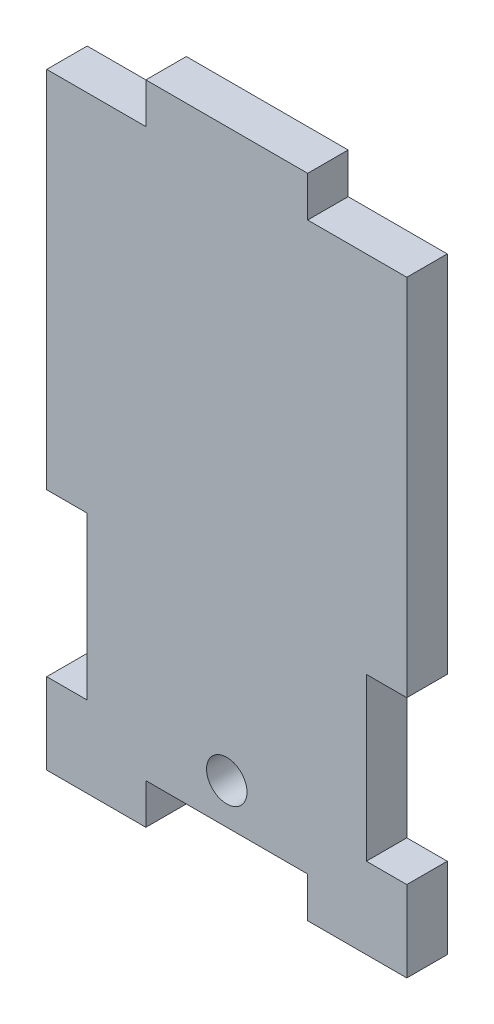
SolidWorks part; units mm, degrees
ref_plane "Front Plane" through (0, 0, 0) normal (0, 0, 1) x (1, 0, 0)
ref_plane "Top Plane" through (0, 0, 0) normal (0, 1, 0) x (1, 0, 0)
ref_plane "Right Plane" through (0, 0, 0) normal (1, 0, 0) x (0, 0, -1)
sketch "Sketch1" plane through (0, 0, 0) normal (0, 0, 1) x (1, 0, 0)
  line L1 (0, 0) -> (44.5, 0)
  line L2 (0, 0) -> (0, 80)
  line L3 (0, 80) -> (44.5, 80)
  line L4 (44.5, 0) -> (44.5, 80)
  line L5 (12.25, 0) -> (32.25, 0)
  line L6 (12.25, 0) -> (12.25, 5)
  line L7 (12.25, 5) -> (32.25, 5)
  line L8 (32.25, 0) -> (32.25, 5)
  line L9 (44.5, 10) -> (39.5, 10)
  line L10 (44.5, 10) -> (44.5, 30)
  line L11 (44.5, 30) -> (39.5, 30)
  line L12 (39.5, 10) -> (39.5, 30)
  line L13 (0, 10) -> (5, 10)
  line L14 (0, 10) -> (0, 30)
  line L15 (0, 30) -> (5, 30)
  line L16 (5, 10) -> (5, 30)
  line L17 (0, 75) -> (12.25, 75)
  line L18 (0, 75) -> (0, 80)
  line L19 (0, 80) -> (12.25, 80)
  line L20 (12.25, 75) -> (12.25, 80)
  line L21 (44.5, 75) -> (32.25, 75)
  line L22 (44.5, 75) -> (44.5, 80)
  line L23 (44.5, 80) -> (32.25, 80)
  line L24 (32.25, 75) -> (32.25, 80)
  circle A0 centre (22.25, 10) radius 2.5
  dimension "D16" = 5
  dimension "D1" = 20
  dimension "D2" = 44.5
  dimension "D3" = 5
  dimension "D4" = 5
  dimension "D5" = 5
  dimension "D6" = 12.25
  dimension "D7" = 20
  dimension "D8" = 20
  dimension "D9" = 80
  dimension "D10" = 30
  dimension "D11" = 10
  dimension "D12" = 5
  dimension "D13" = 12.25
  dimension "D14" = 12.25
  dimension "D15" = 5
  dimension "D17" = 5
  dimension "D18" = 10
extrude "Boss-Extrude1" add sketch "Sketch1" along normal blind 5
